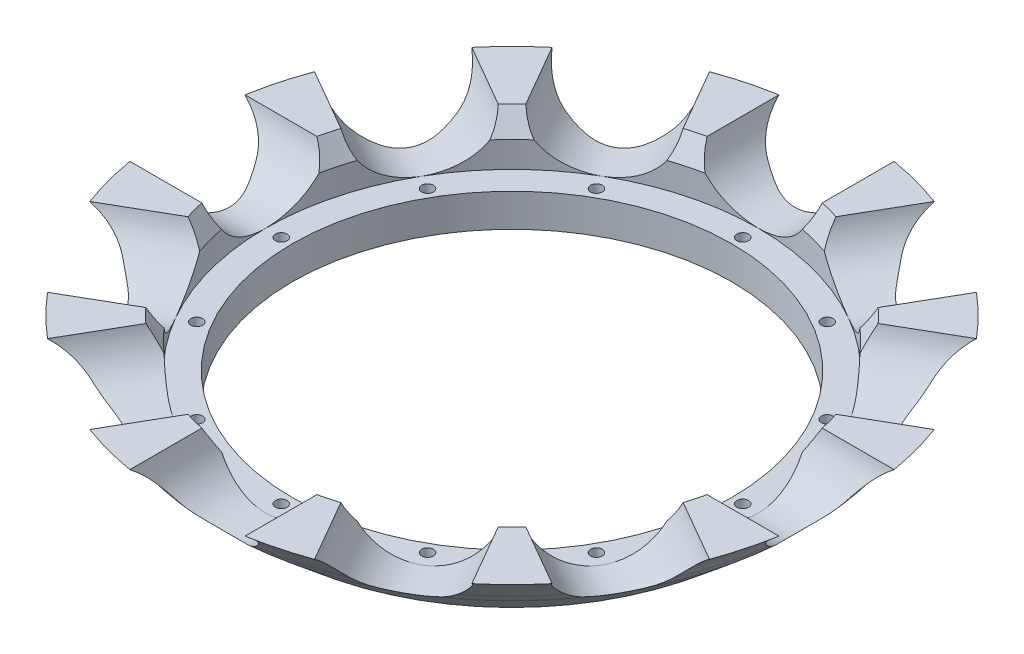
SolidWorks part; units mm, degrees
material "PUR"
ref_plane "Front Plane" through (0, 0, 0) normal (0, 0, 1) x (1, 0, 0)
ref_plane "Top Plane" through (0, 0, 0) normal (0, 1, 0) x (1, 0, 0)
ref_plane "Right Plane" through (0, 0, 0) normal (1, 0, 0) x (0, 0, -1)
sketch "Sketch1" plane through (0, 0, 0) normal (0, 0, 1) x (1, 0, 0)
  line L0 (-60, 9.965) -> (-60, 18.965) construction
  line L1 (-60, 9.965) -> (-60, 18.965)
  line L2 (-66.5, 9.965) -> (-66.5, 18.965) construction
  line L3 (-66.5, 9.965) -> (-66.5, 18.965)
  line L4 (-60, 18.965) -> (-66.5, 18.965)
  line L5 (-60, 9.965) -> (-66.5, 9.965)
  line L6 (0, -200069.0475) -> (0, 200086.9028) construction
  line L7 (0, -200069.0475) -> (0, 200086.9028) construction
revolve "Revolve1" add sketch "Sketch1" angle 360 about L7
sketch "Sketch2" plane through (0, 18.965, 0) normal (0, 1, 0) x (1, 0, 0)
  circle A1 centre (0, 63) radius 1.6
  circle A2 centre (0, 63) radius 1.6
  dimension "D1" = 0
extrude "Cut-Extrude1" cut sketch "Sketch2" against normal through all
pattern_circular "CirPattern1" count 12 over 360 about axis through (0, 0, 0) along (0, 1, 0) of "Cut-Extrude1"
sketch "Sketch3" plane through (0, 0, 0) normal (0, 0, 1) x (1, 0, 0)
  line L0 (-66.5, 18.965) -> (-66.5, 9.965)
  line L1 (-66.5, 9.965) -> (-78.5, 20.0342)
  line L2 (-66.5, 18.965) -> (-67.3, 18.965)
  line L3 (-67.3, 18.965) -> (-67.3, 20.0342)
  line L4 (-67.3, 20.0342) -> (-78.5, 20.0342) construction
  line L5 (-84.0797, 32) -> (-84.0797, 43.6972) construction
  line L6 (-67.3, 20.0342) -> (-67.3, 26.0342)
  line L7 (-84.0797, 32) -> (-90, 32)
  line L8 (0, 0) -> (0, 39.8275) construction
  line L9 (-84.0797, 32) -> (-70.7444, 32)
  line L10 (-70.7444, 32) -> (-67.3, 26.0342)
  arc A0 (-78.5, 20.0342) -> (-81.2743, 23.0684) centre (-68.4595, 32) cw
  arc A3 (-81.2743, 23.0684) -> (-90, 32) centre (-112.4493, 1.3401) ccw
  arc A4 (-81.2743, 23.0684) -> (-84.0797, 32) centre (-68.4595, 32) cw construction
  dimension "D8" = 38
  dimension "D1" = 50
  dimension "D2" = 12
  dimension "D3" = 0.8
  dimension "D4" = 32
  dimension "D5" = 6
  dimension "D6" = 150
  dimension "D7" = 90
revolve "Revolve2" add sketch "Sketch3" angle 360 about L8
sketch "Sketch4" plane through (0, 0, 0) normal (0, 0, 1) x (1, 0, 0)
  line L1 (67.3, 18.965) -> (-67.3, 18.965) construction
  line L2 (67.3, 18.965) -> (-67.3, 18.965) construction
  line L4 (0, 0) -> (0, 34.965) construction
  circle A0 centre (0, 34.965) radius 16
  dimension "D1" = 32
extrude "Cut-Extrude2" cut sketch "Sketch4" along normal through all
pattern_circular "CirPattern2" count 12 over 360 about axis through (0, 9.965, 0) along (0, -1, 0) of "Cut-Extrude2"
